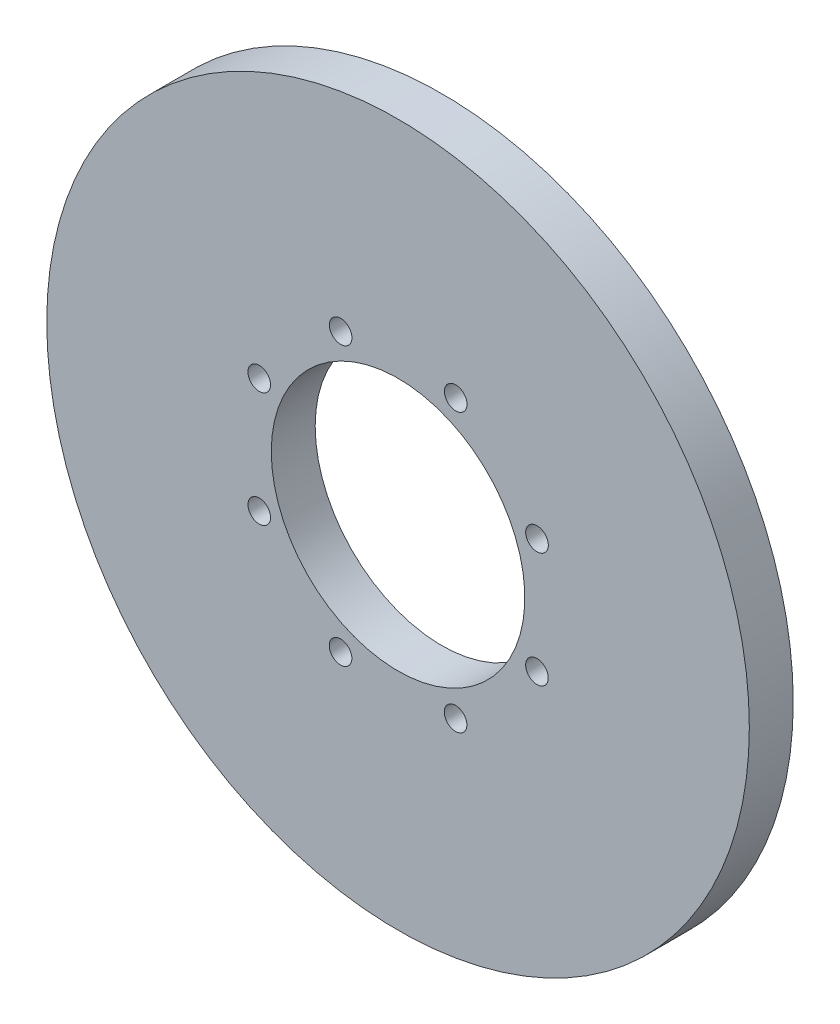
SolidWorks part; units mm, degrees
material "1060 Alloy"
ref_plane "Front Plane" through (0, 0, 0) normal (0, 0, 1) x (1, 0, 0)
ref_plane "Top Plane" through (0, 0, 0) normal (0, 1, 0) x (1, 0, 0)
ref_plane "Right Plane" through (0, 0, 0) normal (1, 0, 0) x (0, 0, -1)
sketch "Sketch1" plane through (0, 0, 0) normal (0, 0, 1) x (1, 0, 0)
  circle A0 centre (0, 0) radius 152.4
  dimension "D1" = 304.8
extrude "Boss-Extrude1" add sketch "Sketch1" along normal blind 19.05
sketch "Sketch2" plane through (0, 0, 0) normal (0, 0, -1) x (-1, 0, 0)
  circle A0 centre (0, 0) radius 65.2 construction
  dimension "D1" = 130.4
hole_wizard "3/8 (0.375) Diameter Hole1" [suppressed] positions "Sketch3" profile "Sketch4" hole size "3/8" standard "ANSI Inch"
sketch "Sketch3" plane through (0, 0, 0) normal (0, 0, -1) x (-1, 0, 0)
  circle A0 centre (0, 0) radius 65.2 construction
  point P0 (-65.2, 0)
sketch "Sketch4" plane through (65.2, 0, 0) normal (1, 0, 0) x (0, 1, 0)
  line L0 (0, 0) -> (0, 20)
  line L1 (0, 20) -> (4.7625, 20)
  line L2 (4.7625, 20) -> (4.7625, 0)
  line L5 (4.7625, 0) -> (0, 0)
  line L11 (0, -6.35) -> (0, 107.95) construction
  dimension "Thru Hole Dia." = 9.525
  dimension "Thru Hole Depth" = 20
pattern_circular "CirPattern1" [suppressed] count 8 over 360
sketch "Sketch5" plane through (0, 0, 0) normal (0, 0, -1) x (-1, 0, 0)
  circle A0 centre (0, 0) radius 55
  dimension "D1" = 110
extrude "Cut-Extrude1" cut sketch "Sketch5" against normal through all
hole_wizard "3/8 Clearance Hole1" positions "Sketch6" profile "Sketch7" hole size "3/8" standard "ANSI Inch" end condition through all
sketch "Sketch6" plane through (0, 0, 19.05) normal (0, 0, 1) x (1, 0, 0)
  line L0 (24.9598, -60.3109) -> (24.96, -60.3104) construction
  line L1 (-24.8875, 60.187) -> (-24.887, 60.1868) construction
  line L2 (25.0149, 60.1642) -> (25.0151, 60.164) construction
  point P0 (60.2851, 24.8617)
  point P3 (60.2623, -25.0404)
  point P24 (-24.9421, -60.2876)
  point P29 (-60.2121, -24.9853)
  point P35 (24.96, -60.3104)
  point P39 (-60.2121, 24.8617)
  point P41 (-24.887, 60.1868)
  point P45 (25.0151, 60.164)
sketch "Sketch7" plane through (60.2851, 24.8617, 19.05) normal (1, 0, 0) x (0, -1, 0)
  line L0 (0, 0) -> (0, 19.05)
  line L1 (0, 19.05) -> (4.9022, 19.05)
  line L2 (4.9022, 19.05) -> (4.9022, 0)
  line L5 (4.9022, 0) -> (0, 0)
  line L11 (0, -6.35) -> (0, 107.95) construction
  dimension "Thru Hole Dia." = 9.8044
  dimension "Thru Hole Depth" = 19.05
